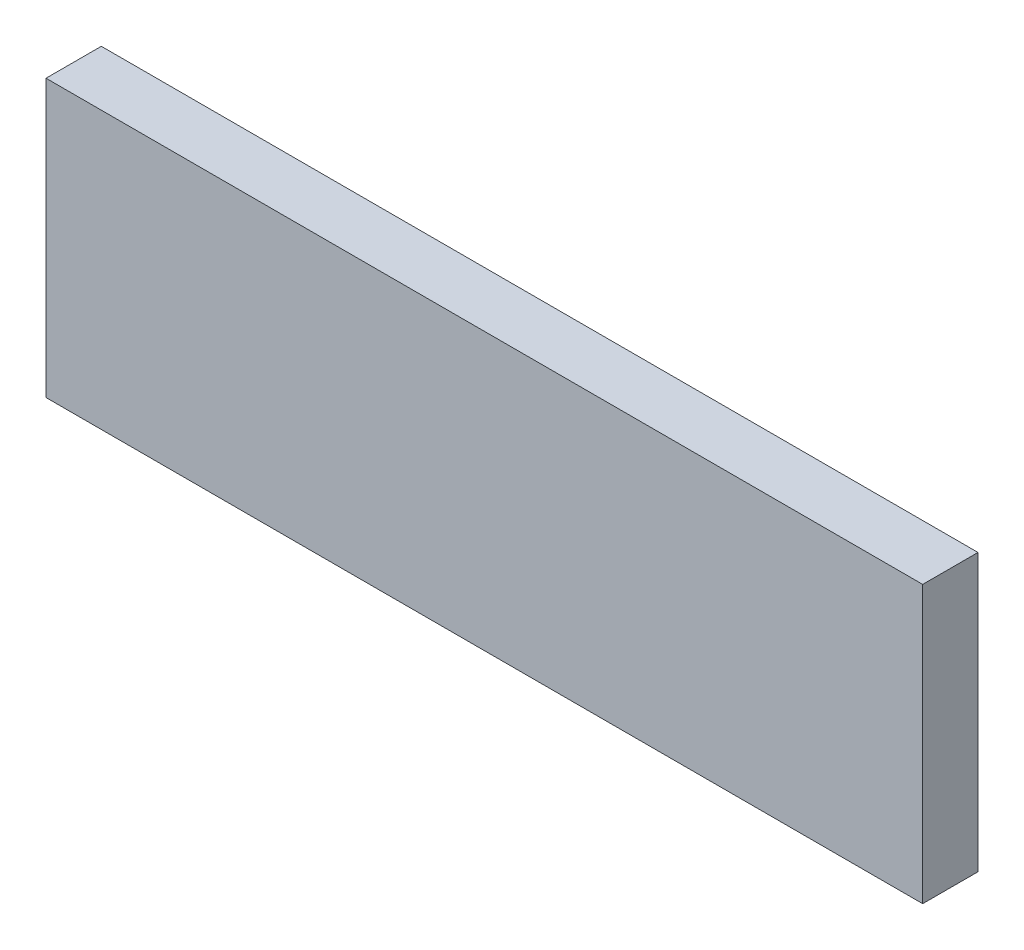
SolidWorks part; units mm, degrees
ref_plane "前视基准面" through (0, 0, 0) normal (0, 0, 1) x (1, 0, 0)
ref_plane "上视基准面" through (0, 0, 0) normal (0, 1, 0) x (1, 0, 0)
ref_plane "右视基准面" through (0, 0, 0) normal (1, 0, 0) x (0, 0, -1)
sketch "草图1" plane through (0, 0, 0) normal (0, 1, 0) x (1, 0, 0)
  line L1 (0, 0) -> (317, 0)
  line L2 (0, 0) -> (0, -20)
  line L3 (0, -20) -> (317, -20)
  line L4 (317, 0) -> (317, -20)
  dimension "D1" = 317
  dimension "D2" = 20
extrude "凸台-拉伸1" add sketch "草图1" along normal blind 100
